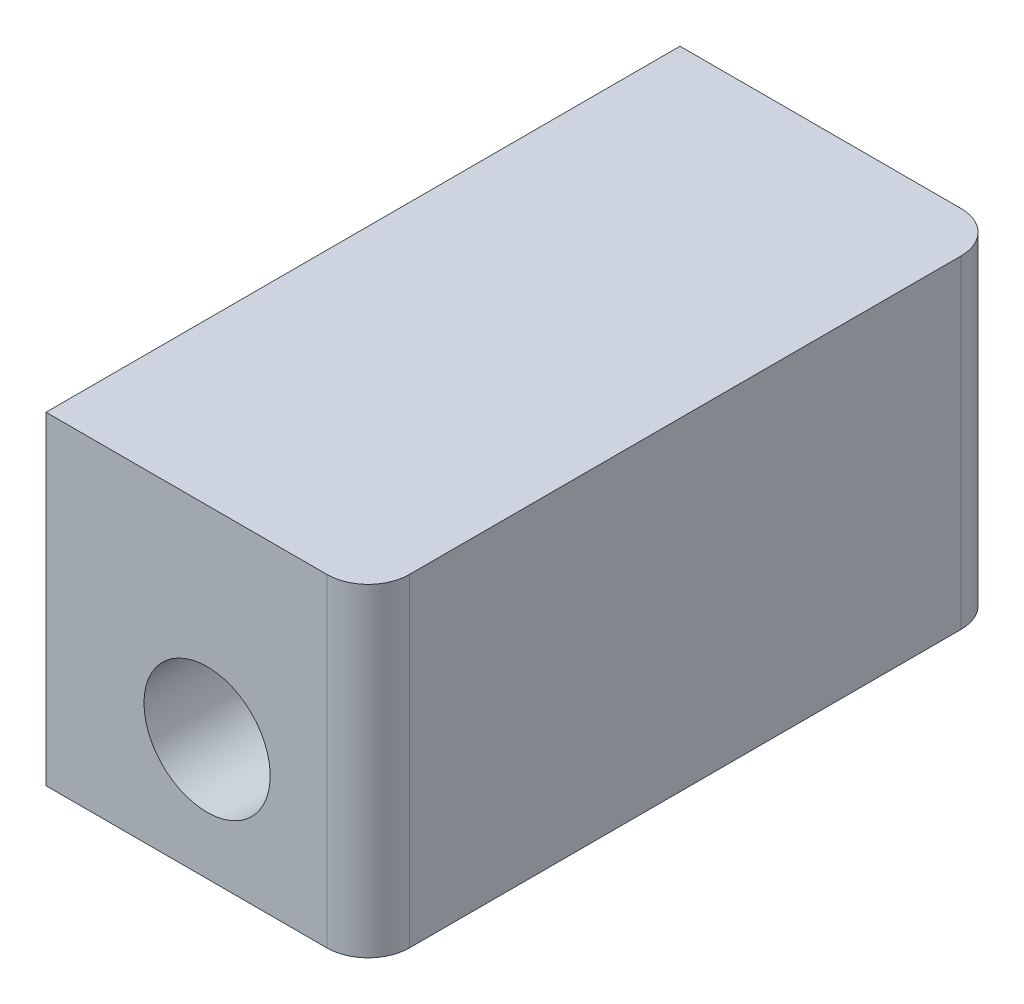
SolidWorks part; units mm, degrees
ref_plane "Front Plane" through (0, 0, 0) normal (0, 0, 1) x (1, 0, 0)
ref_plane "Top Plane" through (0, 0, 0) normal (0, 1, 0) x (1, 0, 0)
ref_plane "Right Plane" through (0, 0, 0) normal (1, 0, 0) x (0, 0, -1)
sketch "Sketch1" plane through (0, 0, 0) normal (0, 1, 0) x (1, 0, 0)
  line L1 (-6.225, -12.25) -> (6.225, -12.25)
  line L2 (-6.225, -12.25) -> (-6.225, 12.25)
  line L3 (-6.225, 12.25) -> (6.225, 12.25)
  line L4 (6.225, -12.25) -> (6.225, 12.25)
  line L5 (-6.225, -12.25) -> (6.225, 12.25) construction
  line L6 (-6.225, 12.25) -> (6.225, -12.25) construction
  point P0 (0, 0)
  dimension "D1" = 12.45
  dimension "D2" = 24.5
extrude "Boss-Extrude1" add sketch "Sketch1" along normal mid plane 12.5
fillet "Fillet1" radius 1.5875 2 edges at (6.225, 0, 12.25) (6.225, 0, -12.25)
sketch "Sketch2" plane through (0, 0, -12.25) normal (0, 0, -1) x (-1, 0, 0)
  line L0 (-4.6375, 6.25) -> (6.225, 6.25) construction
  circle A0 centre (0, -1.5875) radius 2.4384
  point P3 (0, 0)
  point P4 (0.3048, -1.7731)
  point P7 (0, 0)
  point P8 (-3.1557, -1.6235)
  point P9 (0, -1.6235)
  point P10 (-2.8107, -1.6235)
  point P12 (0, 0)
  dimension "D1" = 4.8768
  dimension "D2" = 7.8375
extrude "Cut-Extrude2" cut sketch "Sketch2" against normal through all
